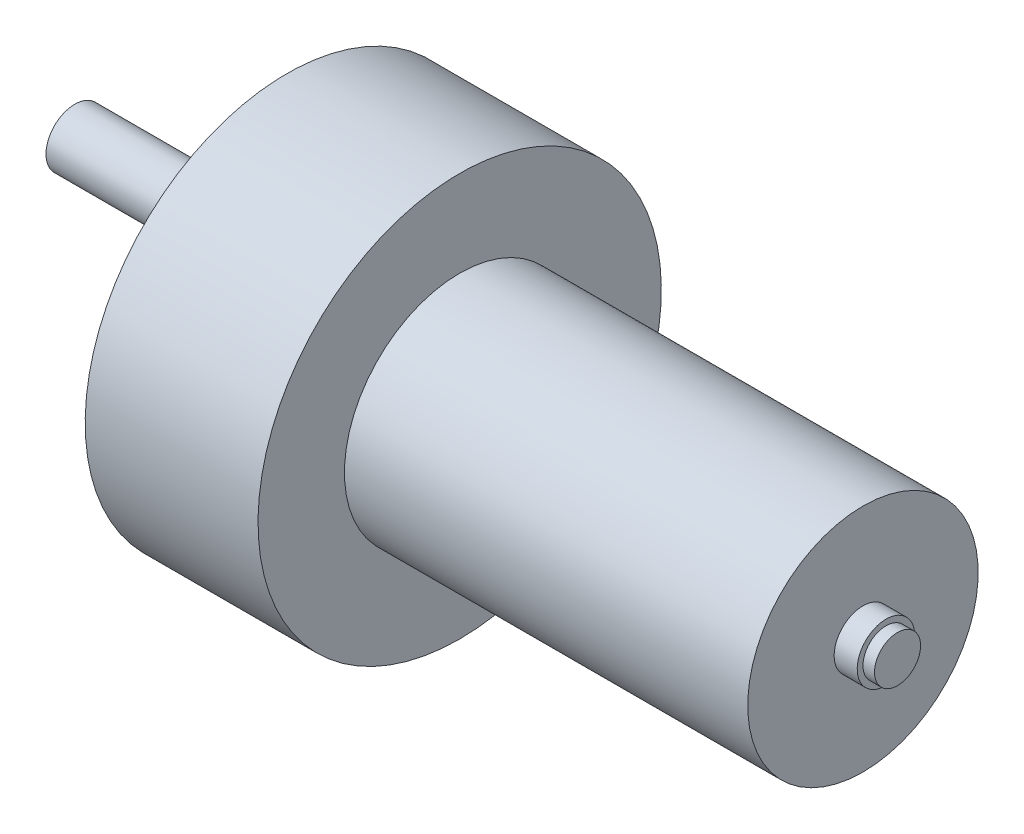
SolidWorks part; units mm, degrees
ref_plane "Front Plane" through (0, 0, 0) normal (0, 0, 1) x (1, 0, 0)
ref_plane "Top Plane" through (0, 0, 0) normal (0, 1, 0) x (1, 0, 0)
ref_plane "Right Plane" through (0, 0, 0) normal (1, 0, 0) x (0, 0, -1)
sketch "Sketch1" plane through (0, 0, 0) normal (0, 0, 1) x (1, 0, 0)
  line L0 (-33.6993, 0) -> (103.5009, 0) construction
  line L1 (70.3007, 5) -> (70.3007, 0)
  line L2 (-33.6993, 35) -> (-3.6993, 35)
  line L3 (-33.6993, 35) -> (-33.6993, 0)
  line L4 (72.3007, 0) -> (72.3007, 4)
  line L5 (-3.6993, 35) -> (-3.6993, 0)
  line L6 (-3.6993, 20) -> (66.3007, 20)
  line L7 (-3.6993, 20) -> (-3.6993, 0)
  line L8 (72.3007, 4) -> (70.3007, 4)
  line L9 (66.3007, 20) -> (66.3007, 0)
  line L10 (66.3007, 5) -> (70.3007, 5)
  line L11 (66.3007, 5) -> (66.3007, 0)
  line L26 (-33.6993, 0) -> (66.3007, 0)
  line L27 (66.3007, 0) -> (72.3007, 0)
  dimension "D1" = 4
  dimension "D2" = 2
  dimension "D3" = 4
  dimension "D4" = 70
  dimension "D5" = 30
  dimension "D6" = 35
  dimension "D7" = 20
revolve "Revolve1" add sketch "Sketch1" angle 360 about L0
sketch "Sketch2" plane through (-33.6993, 0, 0) normal (-1, 0, 0) x (0, 0, 1)
  circle A0 centre (0, 7) radius 6
  dimension "D2" = 12
extrude "Boss-Extrude1" add sketch "Sketch2" along normal blind 6.8
sketch "Sketch3" plane through (-40.4993, 0, 0) normal (-1, 0, 0) x (0, 0, 1)
  circle A0 centre (0, 7) radius 5
  dimension "D1" = 10
extrude "Boss-Extrude2" add sketch "Sketch3" along normal blind 30
sketch "Sketch4" plane through (-33.6993, 0, 0) normal (-1, 0, 0) x (0, 0, 1)
  line L0 (-35, 0) -> (35, 0) construction
  line L1 (0, 35) -> (0, -35) construction
  circle A0 centre (0, 0) radius 35 construction
  circle A1 centre (-15.75, 0) radius 1.5
  circle A2 centre (-7.875, 13.6399) radius 1.5
  circle A3 centre (7.875, 13.6399) radius 1.5
  circle A4 centre (15.75, 0) radius 1.5
  circle A5 centre (7.875, -13.6399) radius 1.5
  circle A6 centre (-7.875, -13.6399) radius 1.5
  point P22 (0, 0)
  dimension "D1" = 3
  dimension "D2" = 15.75
  dimension "D3" = 6
extrude "Cut-Extrude1" cut sketch "Sketch4" against normal blind 3
